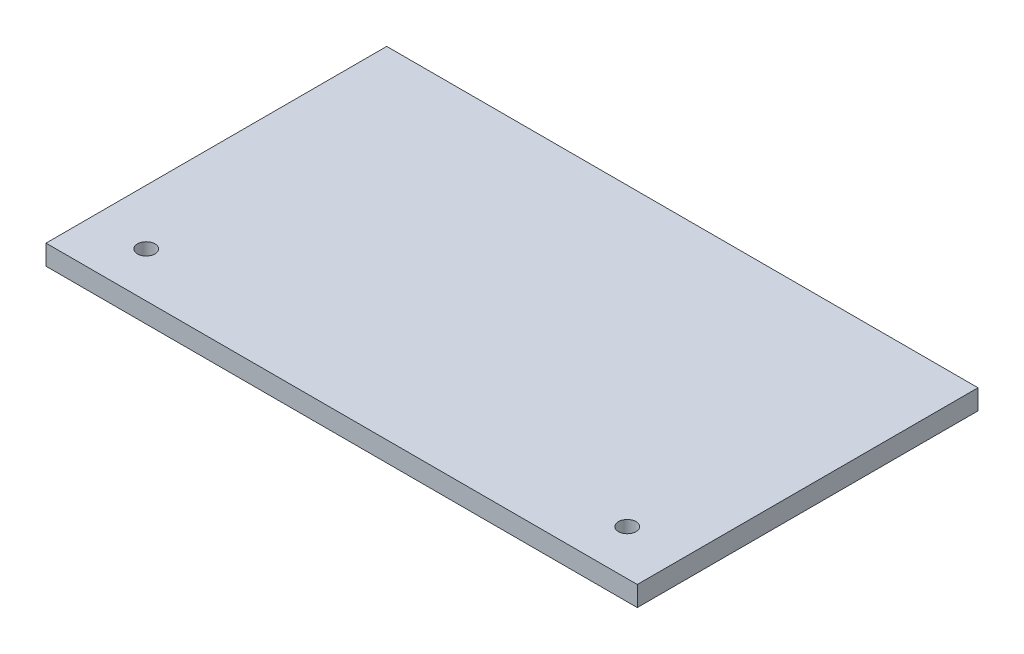
SolidWorks part; units mm, degrees
ref_plane "Front Plane" through (0, 0, 0) normal (0, 0, 1) x (1, 0, 0)
ref_plane "Top Plane" through (0, 0, 0) normal (0, 1, 0) x (1, 0, 0)
ref_plane "Right Plane" through (0, 0, 0) normal (1, 0, 0) x (0, 0, -1)
sketch "Sketch1" plane through (0, 0, 0) normal (0, 1, 0) x (1, 0, 0)
  line L1 (-59, -34) -> (59, -34)
  line L2 (-59, -34) -> (-59, 34)
  line L3 (-59, 34) -> (59, 34)
  line L4 (59, -34) -> (59, 34)
  circle A0 centre (-48, -25) radius 1.75
  circle A1 centre (48, -25) radius 1.75
extrude "Tray_Base_Extrude" add sketch "Sketch1" along normal blind 4
equation "\"ValveDiameter\" = 50mm"
equation "\"MotorGearTeeth\" = 40"
equation "\"OutputGearTeeth\" = 80"
equation "\"GearModule\" = 1.5mm"
equation "\"PressureAngle\" = 20deg"
equation "\"GearCenterDistance\" = 90mm"
equation "\"GearWidth\" = 18mm"
equation "\"OutputShaftDiameter\" = 20mm"
equation "\"BearingOD\" = 47mm"
equation "\"BearingWidth\" = 14mm"
equation "\"PlateThickness\" = 6mm"
equation "\"ValveRotation\" = 90deg"
